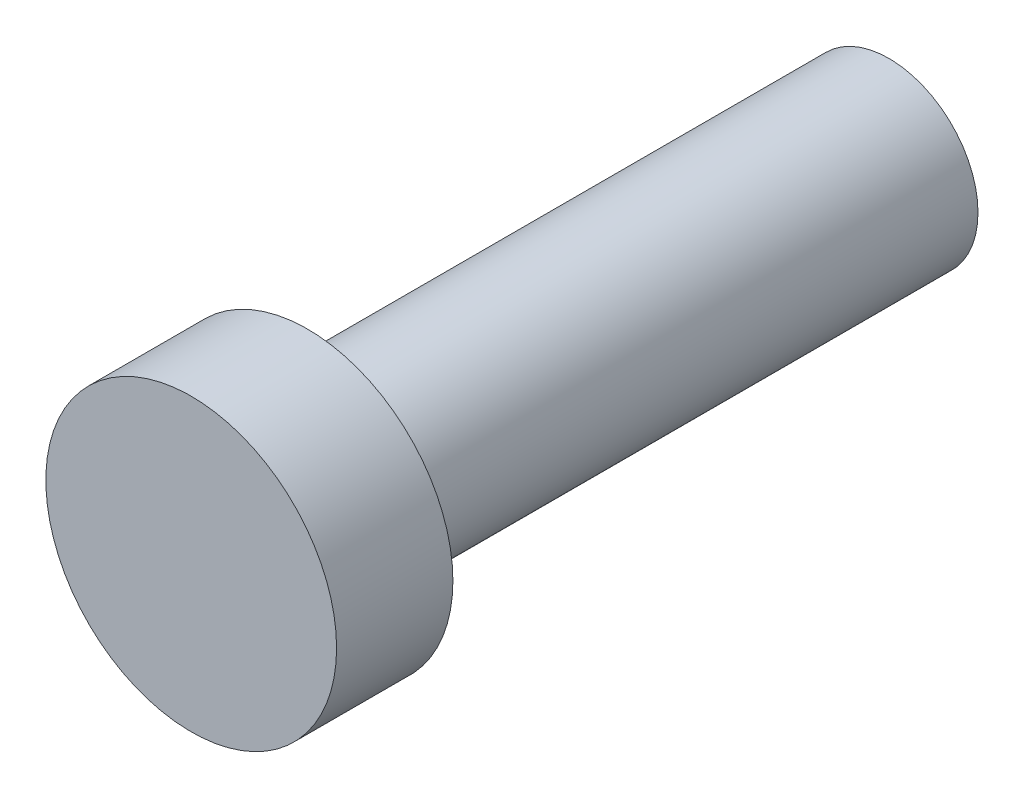
SolidWorks part; units mm, degrees
ref_plane "정면" through (0, 0, 0) normal (0, 0, 1) x (1, 0, 0)
ref_plane "윗면" through (0, 0, 0) normal (0, 1, 0) x (1, 0, 0)
ref_plane "우측면" through (0, 0, 0) normal (1, 0, 0) x (0, 0, -1)
sketch "스케치2" plane through (0, 0, 0) normal (0, 0, 1) x (1, 0, 0)
  circle A0 centre (0, 0) radius 1.53
  dimension "D1" = 3.06
extrude "보스-돌출1" add sketch "스케치2" along normal blind 10
sketch "스케치11" plane through (0, 0, 10) normal (0, 0, 1) x (1, 0, 0)
  circle A0 centre (0, 0) radius 2.5
  dimension "D1" = 5
extrude "보스-돌출2" add sketch "스케치11" along normal blind 2 contours A0
